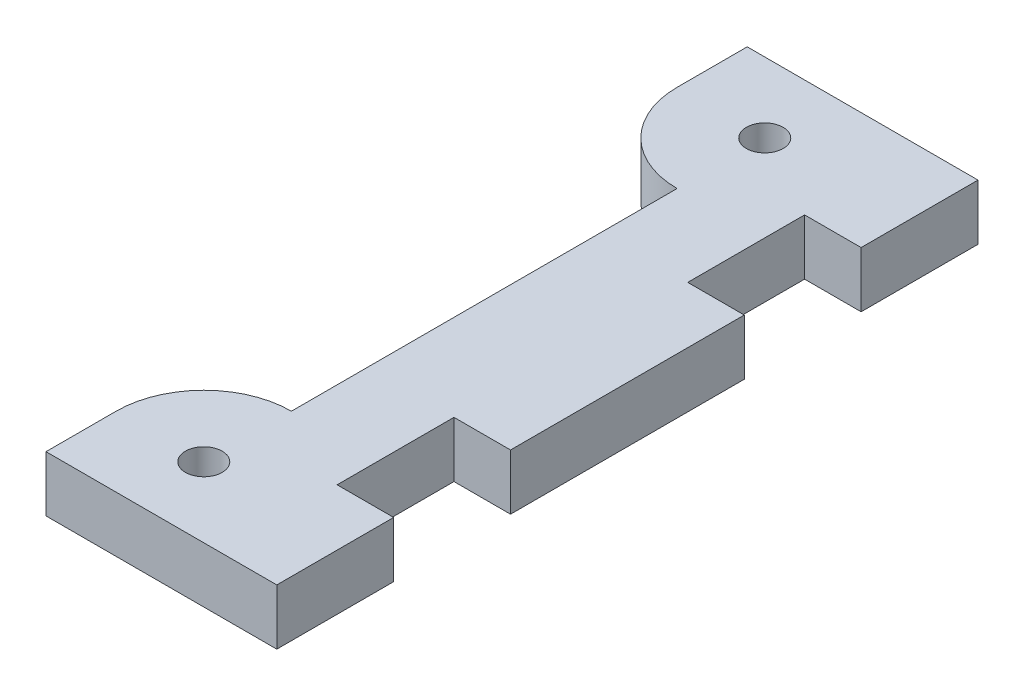
SolidWorks part; units mm, degrees
ref_plane "Alzado" through (0, 0, 0) normal (0, 0, 1) x (1, 0, 0)
ref_plane "Planta" through (0, 0, 0) normal (0, 1, 0) x (1, 0, 0)
ref_plane "Vista lateral" through (0, 0, 0) normal (1, 0, 0) x (0, 0, -1)
sketch "Sketch2" plane through (0, 0, 0) normal (0, 1, 0) x (1, 0, 0)
  line L1 (-44.165, -40) -> (44.165, -40)
  line L2 (-44.165, -40) -> (-44.165, 40)
  line L3 (-44.165, 40) -> (44.165, 40)
  line L4 (44.165, -40) -> (44.165, 40)
  line L5 (-44.165, -40) -> (44.165, 40) construction
  line L6 (-44.165, 40) -> (44.165, -40) construction
  point P0 (0, 0)
  dimension "D1" = 88.33
  dimension "D2" = 80
extrude "Boss-Extrude1" add sketch "Sketch2" along normal blind 6.35
sketch "Sketch3" plane through (0, 6.35, 0) normal (0, 1, 0) x (1, 0, 0)
  line L0 (44.165, -26.6667) -> (37.715, -26.6667)
  line L1 (44.165, -40) -> (44.165, 40) construction
  line L2 (37.715, -26.6667) -> (37.715, -13.3333)
  line L3 (37.715, -13.3333) -> (44.165, -13.3333)
  line L4 (44.165, -13.3333) -> (44.165, -26.6667)
  line L5 (44.165, 0) -> (0, 0) construction
  line L6 (-44.165, -40) -> (44.165, -40) construction
  line L7 (37.715, 13.3333) -> (44.165, 13.3333)
  line L8 (37.715, 26.6667) -> (37.715, 13.3333)
  line L9 (44.165, 26.6667) -> (37.715, 26.6667)
  line L10 (44.165, 13.3333) -> (44.165, 26.6667)
  dimension "D1" = 6.45
  dimension "D2" = 13.3333
  dimension "D3" = 13.3333
extrude "Cut-Extrude1" cut sketch "Sketch3" against normal through all
sketch "Sketch4" plane through (0, 6.35, 0) normal (0, 1, 0) x (1, 0, 0)
  line L3 (27.835, -32) -> (27.835, 32) construction
  line L6 (-36.165, -32) -> (44.165, -32)
  line L7 (-36.165, 32) -> (-36.165, -32)
  line L8 (44.165, 32) -> (-36.165, 32)
  line L9 (-36.165, -32) -> (27.835, -32) construction
  line L10 (-36.165, 32) -> (-36.165, -32) construction
  line L11 (27.835, 32) -> (-36.165, 32) construction
  dimension "D1" = 8
  dimension "D2" = 64
hole_wizard "M5 Tapped Hole1" positions "Sketch5" profile "Sketch6" tap size "M5" standard "ISO" end condition through all
sketch "Sketch5" plane through (0, 6.35, 0) normal (0, 1, 0) x (1, 0, 0)
  point P0 (-36.165, 32)
  point P3 (27.835, 32)
  point P6 (-36.165, -32)
  point P9 (27.835, -32)
sketch "Sketch6" plane through (-36.165, 6.35, -32) normal (1, 0, 0) x (0, 0, 1)
  line L0 (0, 0) -> (0, 6.35)
  line L1 (0, 6.35) -> (2.1, 6.35)
  line L2 (2.1, 6.35) -> (2.1, 0)
  line L5 (2.1, 0) -> (0, 0)
  line L11 (0, -6.35) -> (0, 107.95) construction
  dimension "Thru Tap Drill Dia." = 4.2
  dimension "Thru Tap Drill Depth" = 6.35
cosmetic thread "Hole Thread1" parameters "D2"=5
cosmetic thread "Hole Thread3" parameters "D2"=5
cosmetic thread "Hole Thread4" [suppressed] parameters "D2"=5
cosmetic thread "Hole Thread5" [suppressed] parameters "D2"=5
sketch "Sketch7" plane through (0, 6.35, 0) normal (0, 1, 0) x (1, 0, 0)
  line L0 (-4.165, 32) -> (-4.165, -32) construction
  line L1 (-26.165, 32) -> (-14.165, 32)
  line L2 (27.835, 0) -> (-36.165, 0) construction
  line L3 (-9.165, 27) -> (-9.165, 10)
  line L4 (-36.165, 32) -> (27.835, 32) construction
  line L5 (-14.165, 5) -> (-31.165, 5)
  line L6 (-31.165, -5) -> (-14.165, -5)
  line L7 (-9.165, -10) -> (-9.165, -27)
  line L8 (-14.165, -32) -> (-26.165, -32)
  line L9 (-36.165, -22) -> (-36.165, -10)
  line L10 (-36.165, 32) -> (-36.165, -32) construction
  line L11 (-36.165, -32) -> (27.835, -32) construction
  line L12 (27.835, 32) -> (27.835, -32) construction
  line L13 (-36.165, 10) -> (-36.165, 22)
  line L14 (27.835, 22) -> (27.835, 10)
  line L15 (22.835, 5) -> (5.835, 5)
  line L16 (0.835, 10) -> (0.835, 27)
  line L17 (5.835, 32) -> (17.835, 32)
  line L18 (17.835, -32) -> (5.835, -32)
  line L19 (0.835, -27) -> (0.835, -10)
  line L20 (5.835, -5) -> (22.835, -5)
  line L21 (27.835, -10) -> (27.835, -22)
  arc A0 (-26.165, -32) -> (-36.165, -22) centre (-36.165, -32) ccw
  circle A1 centre (-36.165, -32) radius 2.1 construction
  arc A2 (-9.165, -27) -> (-14.165, -32) centre (-14.165, -27) cw
  arc A3 (-31.165, -5) -> (-36.165, -10) centre (-31.165, -10) ccw
  arc A4 (-14.165, -5) -> (-9.165, -10) centre (-14.165, -10) cw
  arc A5 (-9.165, 27) -> (-14.165, 32) centre (-14.165, 27) ccw
  arc A6 (-9.165, 10) -> (-14.165, 5) centre (-14.165, 10) cw
  arc A7 (-31.165, 5) -> (-36.165, 10) centre (-31.165, 10) cw
  arc A8 (-36.165, 22) -> (-26.165, 32) centre (-36.165, 32) ccw
  arc A9 (22.835, 5) -> (27.835, 10) centre (22.835, 10) ccw
  arc A10 (5.835, 5) -> (0.835, 10) centre (5.835, 10) cw
  arc A11 (0.835, 27) -> (5.835, 32) centre (5.835, 27) cw
  arc A12 (17.835, 32) -> (27.835, 22) centre (27.835, 32) ccw
  arc A13 (0.835, -27) -> (5.835, -32) centre (5.835, -27) ccw
  arc A14 (0.835, -10) -> (5.835, -5) centre (5.835, -10) cw
  arc A15 (22.835, -5) -> (27.835, -10) centre (22.835, -10) cw
  arc A16 (27.835, -22) -> (17.835, -32) centre (27.835, -32) ccw
  point P10 (0, -40)
  point P13 (-4.165, 0)
  point P65 (-4.165, 0)
  dimension "D1" = 5
  dimension "D3" = 10
  dimension "D4" = 5
  dimension "D2" = 5
  dimension "D5" = 4
extrude "Cut-Extrude2" cut sketch "Sketch7" against normal blind 10
sketch "Sketch8" plane through (0, 6.35, 0) normal (0, 1, 0) x (1, 0, 0)
  line L12 (17.835, 45) -> (17.835, 32)
  line L13 (27.835, 22) -> (27.835, -22)
  line L14 (17.835, -32) -> (17.835, -45)
  line L24 (49.165, -45) -> (49.165, -21.6667)
  line L25 (49.165, 45) -> (-49.165, 45)
  line L26 (-49.165, 45) -> (-49.165, -45)
  line L27 (-49.165, -45) -> (49.165, -45)
  line L29 (17.835, 45) -> (-49.165, 45)
  line L30 (-49.165, 45) -> (-49.165, -45)
  line L31 (-49.165, -45) -> (17.835, -45)
  line L32 (49.165, -21.6667) -> (42.715, -21.6667)
  line L34 (42.715, -21.6667) -> (42.715, -18.3333)
  line L36 (42.715, -18.3333) -> (49.165, -18.3333)
  line L38 (49.165, -18.3333) -> (49.165, 18.3333)
  line L40 (49.165, 18.3333) -> (42.715, 18.3333)
  line L42 (42.715, 18.3333) -> (42.715, 21.6667)
  line L44 (42.715, 21.6667) -> (49.165, 21.6667)
  line L46 (49.165, 21.6667) -> (49.165, 45)
  arc A4 (17.835, 32) -> (27.835, 22) centre (27.835, 32) ccw
  arc A5 (27.835, -22) -> (17.835, -32) centre (27.835, -32) ccw
  dimension "D1" = 5
extrude "Cut-Extrude3" cut sketch "Sketch8" against normal up to next
